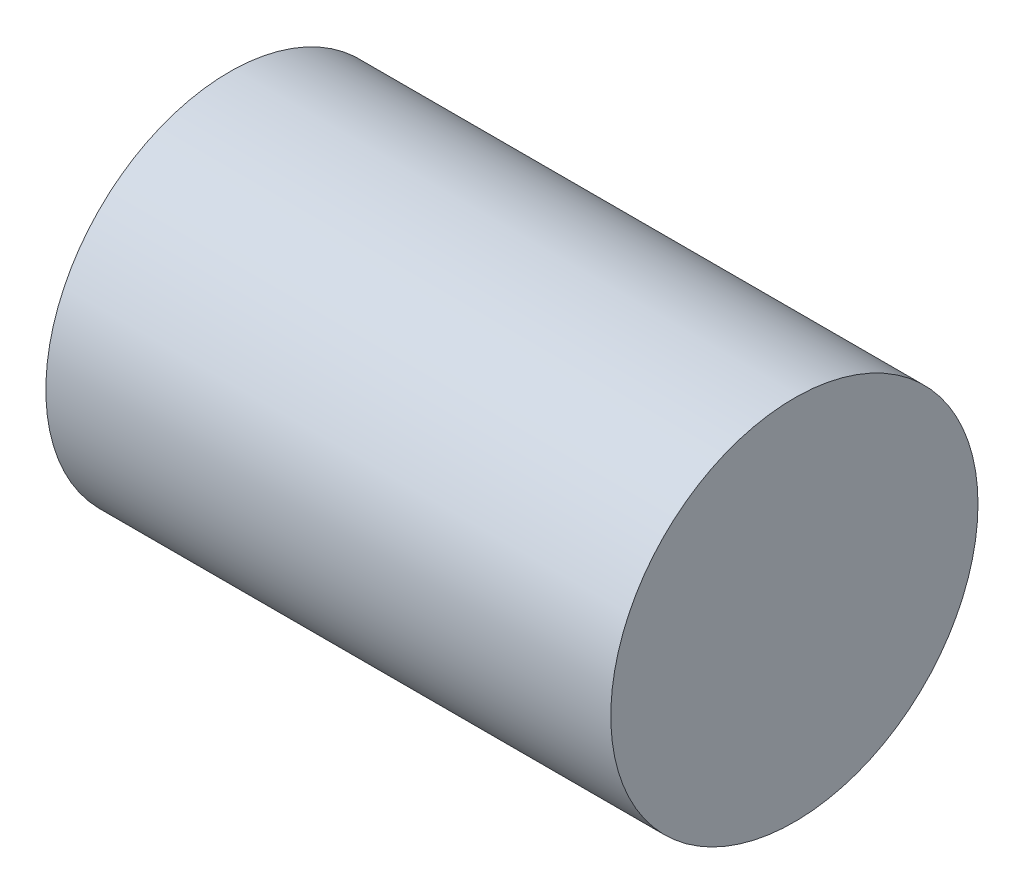
SolidWorks part; units mm, degrees
ref_plane "Front Plane" through (0, 0, 0) normal (0, 0, 1) x (1, 0, 0)
ref_plane "Top Plane" through (0, 0, 0) normal (0, 1, 0) x (1, 0, 0)
ref_plane "Right Plane" through (0, 0, 0) normal (1, 0, 0) x (0, 0, -1)
sketch "Sketch1" plane through (0, 0, 0) normal (1, 0, 0) x (0, 0, -1)
  circle A0 centre (0, 0) radius 26
  dimension "D1" = 52
extrude "Boss-Extrude1" add sketch "Sketch1" along normal blind 80
